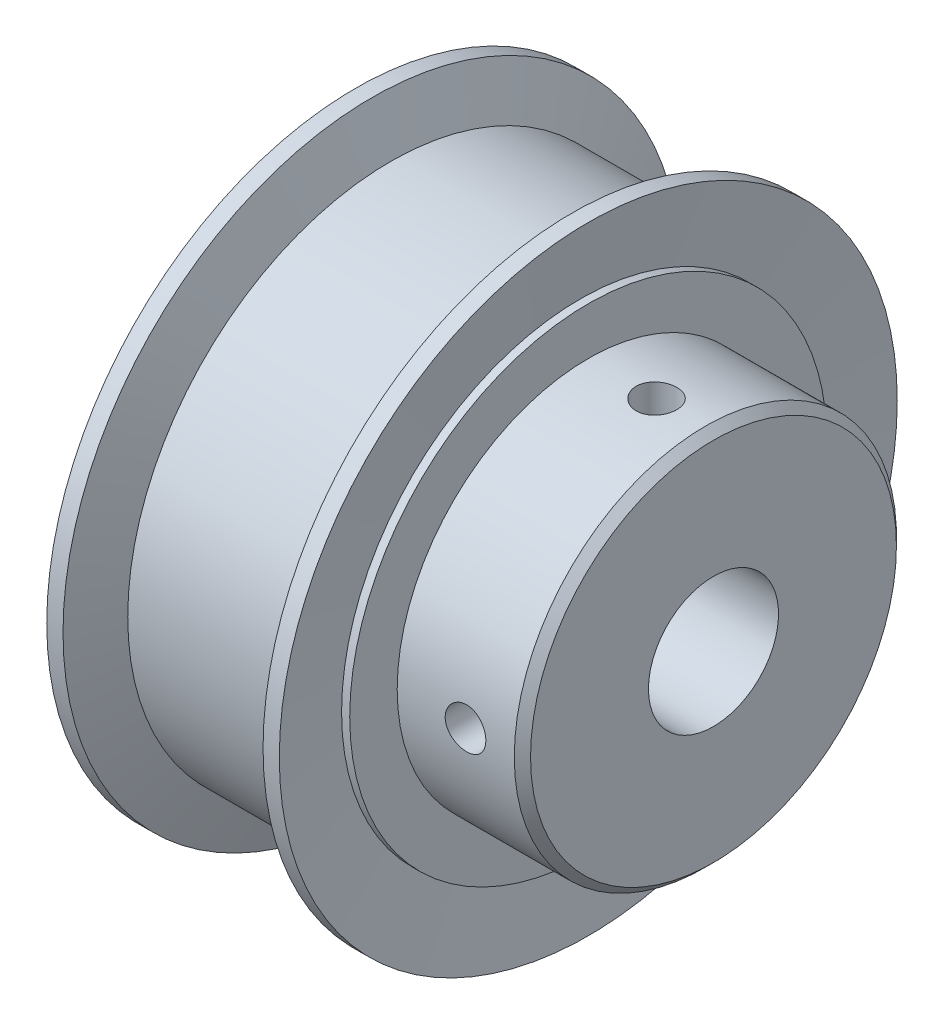
SolidWorks part; units mm, degrees
material "Alliage 1060"
ref_plane "Plan de face" through (0, 0, 0) normal (0, 0, 1) x (1, 0, 0)
ref_plane "Plan de dessus" through (0, 0, 0) normal (0, 1, 0) x (1, 0, 0)
ref_plane "Plan de droite" through (0, 0, 0) normal (1, 0, 0) x (0, 0, -1)
sketch "Sketch1" plane through (0, 0, 0) normal (0, 0, 1) x (1, 0, 0)
  line L0 (0, 0) -> (14.85, 0) construction
  line L1 (-7.15, 4) -> (-7.15, 14.67)
  line L2 (-7.15, 19) -> (-6.15, 19)
  line L3 (-6.15, 19) -> (-5, 16.17)
  line L4 (-5, 16.17) -> (5, 16.17)
  line L5 (5, 16.17) -> (6.15, 19)
  line L6 (6.15, 19) -> (7.15, 19)
  line L7 (7.15, 14.67) -> (7.15, 11.75)
  line L8 (7.15, 11.75) -> (14.85, 11.75)
  line L9 (14.85, 11.75) -> (14.85, 4)
  line L10 (14.85, 4) -> (-7.15, 4)
  line L11 (-6.15, 19) -> (6.15, 19) construction
  line L12 (0, 16.17) -> (0, 19) construction
  line L13 (-7.15, 14.67) -> (-6.65, 14.67)
  line L14 (-6.65, 14.67) -> (-7.15, 19)
  line L15 (6.65, 14.67) -> (7.15, 19)
  line L16 (7.15, 14.67) -> (6.65, 14.67)
  dimension "D1" = 8
  dimension "D2" = 23.5
  dimension "D3" = 32.34
  dimension "D4" = 38
  dimension "D5" = 10
  dimension "D6" = 1.5
  dimension "D7" = 14.3
  dimension "D8" = 22
  dimension "D9" = 0.5
  dimension "D10" = 1
revolve "Revolve1" add sketch "Sketch1" angle 360 about L0
chamfer "Chamfer1" distance 0.5 angle 45 1 edges at (14.85, 0, 11.75)
hole_wizard "Trou taraudé M30" positions "3DSketch1" profile "Sketch2" tap size "M3" standard "ISO"
sketch3d "3DSketch1"
  point P0 (11.35, 0, 11.75)
  dimension "D1" = 3.5
cosmetic thread "Cosmetic Thread1" parameters "D2"=3
sketch "Sketch2" plane through (11.35, 0, 11.75) normal (1, 0, 0) x (0, -1, 0)
  line L0 (0, 0) -> (0, 23.5)
  line L1 (0, 23.5) -> (1.25, 23.5)
  line L2 (1.25, 23.5) -> (1.25, 0)
  line L5 (1.25, 0) -> (0, 0)
  line L11 (0, -6.35) -> (0, 107.95) construction
  dimension "Diamètre du trou pour taraudage jusqu'au prochain" = 2.5
  dimension "Profondeur du trou pour taraudage jusqu'au prochain" = 23.5
pattern_circular "CirPattern1" count 2 every 90 about axis through (7.15, 0, 0) along (-1, 0, 0) of "Trou taraudé M30"
